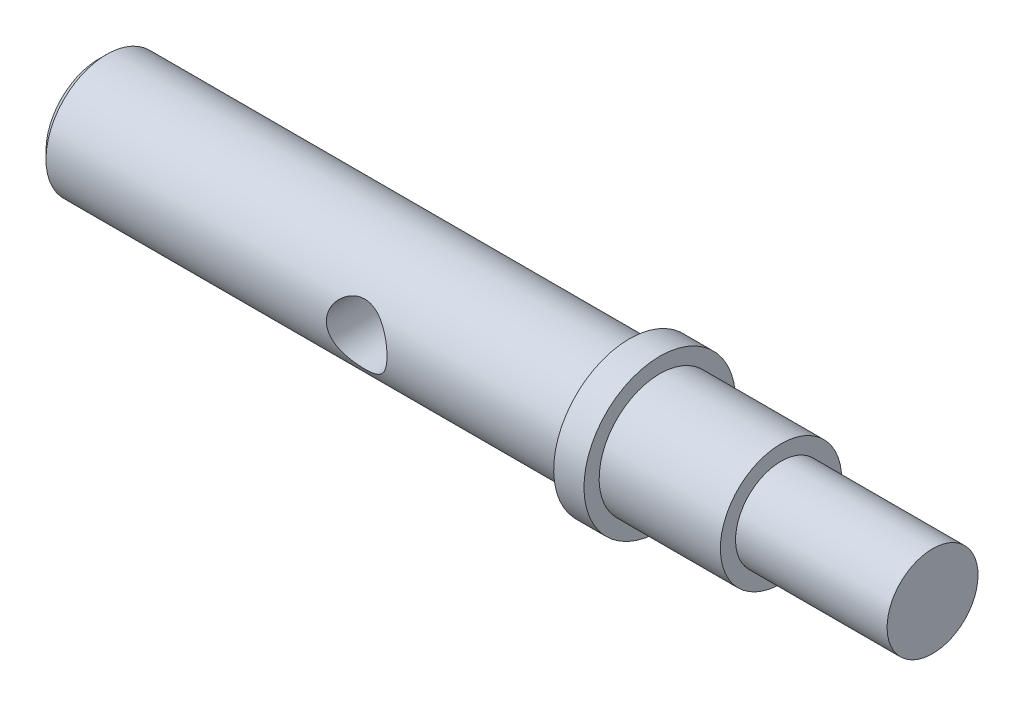
SolidWorks part; units mm, degrees
ref_plane "前视基准面" through (0, 0, 0) normal (0, 0, 1) x (1, 0, 0)
ref_plane "上视基准面" through (0, 0, 0) normal (0, 1, 0) x (1, 0, 0)
ref_plane "右视基准面" through (0, 0, 0) normal (1, 0, 0) x (0, 0, -1)
sketch "草图1" plane through (0, 0, 0) normal (0, 0, 1) x (1, 0, 0)
  line L0 (-16.7018, 0) -> (17, 0)
  line L1 (0, 0) -> (0, 2)
  line L2 (0, 2) -> (4, 2)
  line L3 (4, 2) -> (4, 4)
  line L4 (4, 4) -> (17, 4)
  line L5 (17, 4) -> (17, 2)
  line L6 (17, 2) -> (21, 2)
  line L7 (21, 2) -> (21, 0)
  line L8 (21, 0) -> (17, 0)
  dimension "D1" = 2
  dimension "D2" = 2
  dimension "D3" = 4
  dimension "D4" = 13
  dimension "D5" = 4
  dimension "D6" = 4
revolve "旋转2" add sketch "草图1" angle 360 about L0
sketch "草图2" plane through (0, 0, 0) normal (0, 0, 1) x (1, 0, 0)
  line L0 (17, 4) -> (4, 4)
  line L1 (12.5, -5.8272) -> (8.5, -5.8272)
  line L2 (12.5, -5.8272) -> (12.5, 5.8272)
  line L3 (12.5, 5.8272) -> (8.5, 5.8272)
  line L4 (8.5, -5.8272) -> (8.5, 5.8272)
  line L6 (12.5, 5.8272) -> (11.8729, 4) construction
  line L7 (17, 4) -> (4, 4) construction
  line L8 (10.5, 4) -> (10.5, 4.8104)
  line L9 (9.1271, 4) -> (8.5, 5.8272) construction
  dimension "D2" = 4
  dimension "D3" = 2
extrude "切除-拉伸1" cut sketch "草图2" against normal blind 10 from offset 3.5 contours L4 L1 L2 L0 offset against normal yes
sketch "草图3" plane through (0, 0, 0) normal (0, 1, 0) x (1, 0, 0)
  line L0 (8.5, 3.5) -> (12.5, 3.5) construction
  line L1 (12.5, 13.3353) -> (8.5, 13.3353)
  line L2 (12.5, 13.3353) -> (12.5, -6.3353)
  line L3 (12.5, -6.3353) -> (8.5, -6.3353)
  line L4 (8.5, 13.3353) -> (8.5, -6.3353)
  line L5 (12.5, 13.3353) -> (8.5, -6.3353) construction
  line L6 (12.5, -6.3353) -> (8.5, 13.3353) construction
  point P0 (10.5, 3.5)
  dimension "D1" = 4
extrude "切除-拉伸2" cut sketch "草图3" against normal blind 10 from offset 3.5 offset against normal yes
sketch "草图4" plane through (21, 0, 0) normal (1, 0, 0) x (0, 0, -1)
  circle A1 centre (0, 0) radius 2
  circle A2 centre (0, 0) radius 2
  circle A3 centre (0, 0) radius 4
  circle A4 centre (0, 0) radius 4
  dimension "D1" = 0
  dimension "D2" = 0
extrude "切除-拉伸3" cut sketch "草图4" against normal blind 29
sketch "草图5" plane through (0, 0, 0) normal (0, 0, 1) x (1, 0, 0)
  circle A0 centre (10.5, 0) radius 1
  dimension "D1" = 2
extrude "切除-拉伸4" cut sketch "草图5" against normal mid plane 10
sketch "草图6" plane through (21, 0, 0) normal (1, 0, 0) x (0, 0, -1)
  circle A1 centre (0, 0) radius 2
  circle A2 centre (0, 0) radius 2
  dimension "D1" = 0
extrude "凸台-拉伸1" add sketch "草图6" along normal blind 1
sketch "草图7" plane through (22, 0, 0) normal (1, 0, 0) x (0, 0, -1)
  circle A0 centre (0, 0) radius 2.5
  circle A1 centre (0, 0) radius 2
  circle A2 centre (0, 0) radius 2
  dimension "D1" = 0
  dimension "D2" = 0.5
extrude "凸台-拉伸2" add sketch "草图7" against normal blind 1 from offset 3.5 offset against normal yes
chamfer "倒角2" distance 0.25 1 edges at (0, -2, 0)
sketch "草图8" plane through (22, 0, 0) normal (1, 0, 0) x (0, 0, -1)
  circle A1 centre (0, 0) radius 2
  circle A2 centre (0, 0) radius 2
  dimension "D1" = 0
extrude "凸台-拉伸3" add sketch "草图8" along normal blind 0.5
sketch "草图11" plane through (22.5, 0, 0) normal (1, 0, 0) x (0, 0, -1)
  circle A0 centre (0, 0) radius 1.5
  dimension "D1" = 3
extrude "凸台-拉伸4" add sketch "草图11" along normal blind 5
